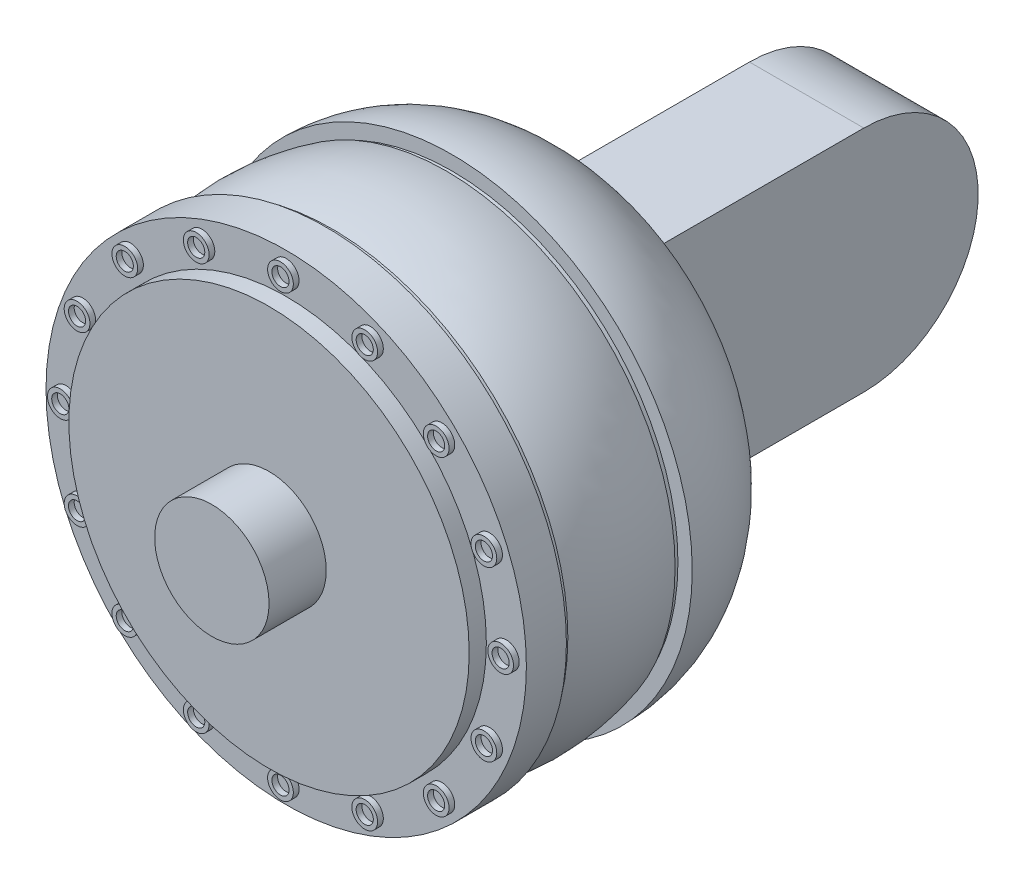
SolidWorks part; units mm, degrees
ref_plane "Front Plane" through (0, 0, 0) normal (0, 0, 1) x (1, 0, 0)
ref_plane "Top Plane" through (0, 0, 0) normal (0, 1, 0) x (1, 0, 0)
ref_plane "Right Plane" through (0, 0, 0) normal (1, 0, 0) x (0, 0, -1)
sketch "Sketch1" plane through (0, 0, 0) normal (0, 1, 0) x (1, 0, 0)
  line L0 (0, 0) -> (0, -20)
  line L1 (0, -20) -> (-42, -20)
  line L2 (-32, 0) -> (0, 0)
  arc A0 (-42, -20) -> (-32, 0) centre (-17, -20) cw
  dimension "D3" = 25
  dimension "D1" = 42
  dimension "D2" = 20
revolve "Revolve1" add sketch "Sketch1" angle 360 about L0
sketch "Sketch2" plane through (0, 0, 20) normal (0, 0, 1) x (1, 0, 0)
  circle A0 centre (0, 0) radius 39.5
  dimension "D1" = 79
extrude "Boss-Extrude1" add sketch "Sketch2" along normal blind 1
sketch "Sketch3" plane through (0, 0, 0) normal (0, 1, 0) x (1, 0, 0)
  line L0 (0, -21) -> (-40, -21)
  line L1 (-39.5, -21) -> (39.5, -21) construction
  line L2 (0, -21) -> (0, -41)
  line L3 (0, -41) -> (-40, -41)
  arc A0 (-40, -21) -> (-40, -41) centre (-4.377, -31) ccw
  dimension "D3" = 37
  dimension "D1" = 40
  dimension "D2" = 20
  dimension "D4" = 40
revolve "Revolve2" add sketch "Sketch3" angle 360 about L2
sketch "Sketch4" plane through (0, 0, 41) normal (0, 0, 1) x (1, 0, 0)
  circle A0 centre (0, 0) radius 41.25
  dimension "D1" = 82.5
extrude "Boss-Extrude2" add sketch "Sketch4" along normal blind 1
sketch "Sketch5" plane through (0, 0, 42) normal (0, 0, 1) x (1, 0, 0)
  circle A0 centre (0, 0) radius 42
  dimension "D1" = 84
extrude "Boss-Extrude3" add sketch "Sketch5" along normal blind 7
sketch "Sketch6" plane through (0, 0, 49) normal (0, 0, 1) x (1, 0, 0)
  circle A0 centre (0, 0) radius 35
  dimension "D1" = 70
extrude "Boss-Extrude4" add sketch "Sketch6" along normal blind 3
sketch "Sketch8" plane through (0, 0, 49) normal (0, 0, 1) x (1, 0, 0)
  line L0 (35, 0) -> (42, 0) construction
  circle A0 centre (0, 0) radius 35 construction
  circle A1 centre (0, 0) radius 35 construction
  circle A2 centre (0, 0) radius 42 construction
  circle A3 centre (38.5, 0) radius 2.25
  circle A4 centre (38.5, 0) radius 1.5
  dimension "D1" = 3
  dimension "D2" = 4.5
extrude "Boss-Extrude5" add sketch "Sketch8" along normal blind 1
pattern_circular "CirPattern1" count 16 over 360 about axis through (0, 0, 0) along (0, 0, 1) of "Boss-Extrude5"
sketch "Sketch9" plane through (0, 0, 0) normal (0, 0, -1) x (-1, 0, 0)
  line L1 (-10, 20) -> (10, 20)
  line L2 (-10, 20) -> (-10, -20)
  line L3 (-10, -20) -> (10, -20)
  line L4 (10, 20) -> (10, -20)
  line L5 (-10, 20) -> (10, -20) construction
  line L6 (-10, -20) -> (10, 20) construction
  point P0 (0, 0)
  dimension "D1" = 20
  dimension "D2" = 40
extrude "Boss-Extrude6" add sketch "Sketch9" along normal blind 42
sketch "Sketch10" plane through (-10, 0, 0) normal (-1, 0, 0) x (0, 0, 1)
  line L0 (-42, -20) -> (-42, 20) construction
  circle A0 centre (-42, 0) radius 20
  dimension "D1" = 40
extrude "Boss-Extrude7" add sketch "Sketch10" against normal up to surface (20 mm away) up to face at (10, 0, -21)
sketch "Sketch11" plane through (-10, 0, 0) normal (-1, 0, 0) x (0, 0, 1)
  circle A0 centre (-42, 0) radius 10
  dimension "D1" = 20
extrude "Boss-Extrude8" add sketch "Sketch11" along normal blind 10
sketch "Sketch12" plane through (0, 0, 52) normal (0, 0, 1) x (1, 0, 0)
  circle A0 centre (0, 0) radius 10
  dimension "D1" = 20
extrude "Boss-Extrude10" add sketch "Sketch12" along normal blind 10
